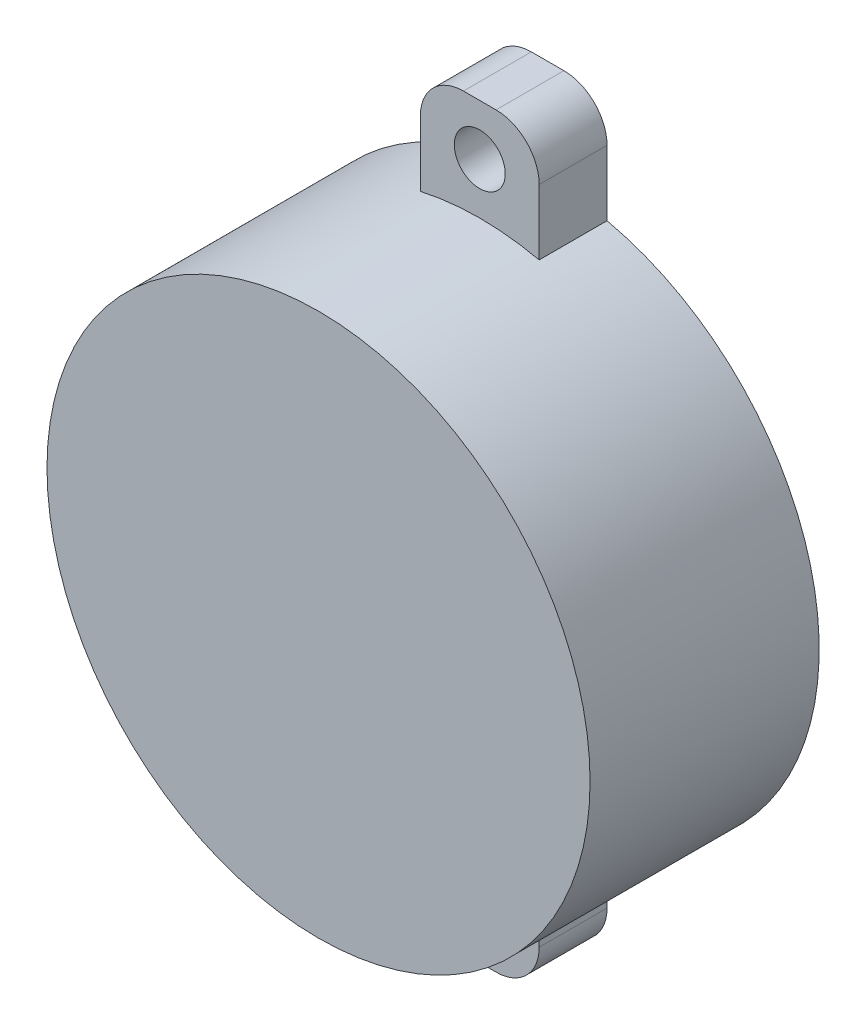
SolidWorks part; units mm, degrees
ref_plane "Front Plane" through (0, 0, 0) normal (0, 0, 1) x (1, 0, 0)
ref_plane "Top Plane" through (0, 0, 0) normal (0, 1, 0) x (1, 0, 0)
ref_plane "Right Plane" through (0, 0, 0) normal (1, 0, 0) x (0, 0, -1)
sketch "Sketch1" plane through (0, 0, 0) normal (0, 0, 1) x (1, 0, 0)
  circle A0 centre (0, 0) radius 16
  dimension "D1" = 32
extrude "Boss-Extrude1" add sketch "Sketch1" along normal blind 13.5
sketch "Sketch2" plane through (0, 0, 0) normal (0, 0, -1) x (-1, 0, 0)
  line L1 (-3.5, 22) -> (3.5, 22)
  line L2 (-3.5, 22) -> (-3.5, -22)
  line L3 (-3.5, -22) -> (3.5, -22)
  line L4 (3.5, 22) -> (3.5, -22)
  line L5 (-3.5, 22) -> (3.5, -22) construction
  line L6 (-3.5, -22) -> (3.5, 22) construction
  point P0 (0, 0)
  dimension "D1" = 44
  dimension "D2" = 7
extrude "Boss-Extrude2" add sketch "Sketch2" against normal blind 4
fillet "Fillet1" radius 2.54 4 edges at (3.5, 22, 2) (-3.5, 22, 2) (3.5, -22, 2) (-3.5, -22, 2)
sketch "Sketch4" plane through (0, 0, 0) normal (0, 0, -1) x (-1, 0, 0)
  line L0 (0, 0) -> (0, -19) construction
  circle A0 centre (0, -19) radius 1.5
  dimension "D1" = 3
  dimension "D2" = 19
extrude "Cut-Extrude1" cut sketch "Sketch4" against normal through all
mirror "Mirror1" about plane through (0, 0, 0) normal (0, 1, 0) of "Cut-Extrude1"
